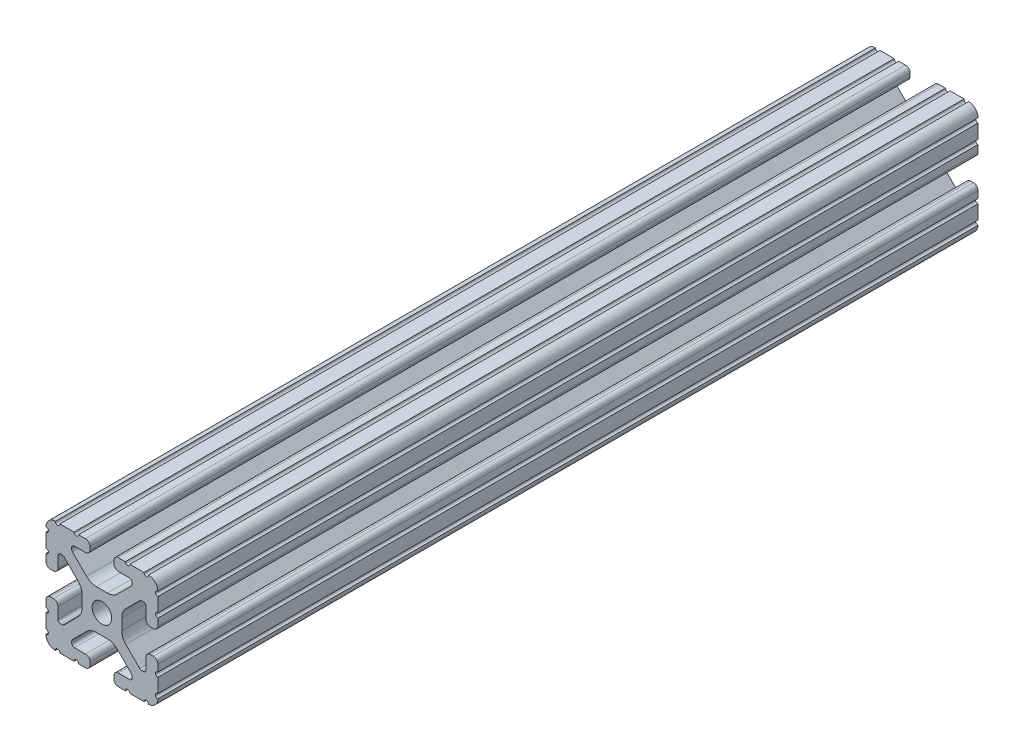
SolidWorks part; units mm, degrees
material "6061 Alloy"
ref_plane "Front Plane" through (0, 0, 0) normal (0, 0, 1) x (1, 0, 0)
ref_plane "Top Plane" through (0, 0, 0) normal (0, 1, 0) x (1, 0, 0)
ref_plane "Right Plane" through (0, 0, 0) normal (1, 0, 0) x (0, 0, -1)
sketch "Sketch1" plane through (0, 0, 0) normal (0, 0, 1) x (1, 0, 0)
  line L0 (0, 25.6181) -> (0, -24.623) construction
  line L1 (-20.8943, 0) -> (20.4607, 0) construction
  line L2 (-10.0229, 12.9148) -> (-5.2522, 8.144)
  line L3 (-10.287, 14.0843) -> (-10.287, 13.5524)
  line L4 (-5.6176, 14.986) -> (-9.3853, 14.986)
  line L5 (-4.064, 17.4964) -> (-4.064, 16.5396)
  line L6 (-7.9742, 19.05) -> (-5.6176, 19.05)
  line L7 (-14.3277, 19.05) -> (-9.4982, 19.05)
  line L8 (-19.05, 9.4961) -> (-19.05, 14.3277)
  line L9 (-19.05, 5.6176) -> (-19.05, 7.9763)
  line L10 (-16.5396, 4.064) -> (-17.4964, 4.064)
  line L11 (-14.986, 9.3853) -> (-14.986, 5.6176)
  line L12 (-13.516, 10.287) -> (-14.0843, 10.287)
  line L13 (-8.1476, 5.2921) -> (-12.8784, 10.0229)
  line L14 (-6.7564, -1.9335) -> (-6.7564, 1.9335)
  line L15 (-12.8784, -10.0229) -> (-8.1476, -5.2921)
  line L16 (-14.0843, -10.287) -> (-13.516, -10.287)
  line L17 (-14.986, -5.6176) -> (-14.986, -9.3853)
  line L18 (-17.4964, -4.064) -> (-16.5396, -4.064)
  line L19 (-19.05, -7.9763) -> (-19.05, -5.6176)
  line L20 (-19.05, -14.3277) -> (-19.05, -9.4961)
  line L21 (-9.4961, -19.05) -> (-14.3277, -19.05)
  line L22 (-5.6176, -19.05) -> (-7.9763, -19.05)
  line L23 (-4.064, -17.4964) -> (-4.064, -16.5396)
  line L24 (10.0229, -12.9148) -> (5.2522, -8.144)
  line L25 (10.287, -14.0843) -> (10.287, -13.5524)
  line L26 (5.6176, -14.986) -> (9.3853, -14.986)
  line L28 (-1.9022, 6.7564) -> (1.9022, 6.7564)
  line L29 (-1.9022, -6.7564) -> (1.9022, -6.7564)
  line L31 (-5.6176, -14.986) -> (-9.3853, -14.986)
  line L32 (-10.287, -14.0843) -> (-10.287, -13.5524)
  line L33 (-10.0229, -12.9148) -> (-5.2522, -8.144)
  line L66 (4.064, -16.5396) -> (4.064, -17.4964)
  line L67 (5.6176, -19.05) -> (7.9763, -19.05)
  line L68 (9.4961, -19.05) -> (14.3277, -19.05)
  line L69 (19.05, -14.3277) -> (19.05, -9.4961)
  line L70 (19.05, -7.9763) -> (19.05, -5.6176)
  line L71 (17.4964, -4.064) -> (16.5396, -4.064)
  line L72 (14.986, -5.6176) -> (14.986, -9.3853)
  line L73 (14.0843, -10.287) -> (13.516, -10.287)
  line L74 (12.8784, -10.0229) -> (8.1476, -5.2921)
  line L75 (6.7564, -1.9335) -> (6.7564, 1.9335)
  line L76 (8.1476, 5.2921) -> (12.8784, 10.0229)
  line L77 (13.516, 10.287) -> (14.0843, 10.287)
  line L78 (14.986, 9.3853) -> (14.986, 5.6176)
  line L79 (16.5396, 4.064) -> (17.4964, 4.064)
  line L80 (19.05, 5.6176) -> (19.05, 7.9763)
  line L81 (19.05, 9.4961) -> (19.05, 14.3277)
  line L82 (14.3277, 19.05) -> (9.4982, 19.05)
  line L83 (7.9742, 19.05) -> (5.6176, 19.05)
  line L84 (4.064, 17.4964) -> (4.064, 16.5396)
  line L85 (5.6176, 14.986) -> (9.3853, 14.986)
  line L86 (10.287, 14.0843) -> (10.287, 13.5524)
  line L87 (10.0229, 12.9148) -> (5.2522, 8.144)
  arc A0 (-10.0229, 12.9148) -> (-10.287, 13.5524) centre (-9.3853, 13.5524) cw
  circle A1 centre (0, 0) radius 3.3274
  arc A2 (-10.287, 14.0843) -> (-9.3853, 14.986) centre (-9.3853, 14.0843) cw
  arc A3 (-4.064, 16.5396) -> (-5.6176, 14.986) centre (-5.6176, 16.5396) cw
  arc A4 (-5.6176, 19.05) -> (-4.064, 17.4964) centre (-5.6176, 17.4964) cw
  arc A5 (-7.9742, 19.05) -> (-9.4982, 19.05) centre (-8.7362, 19.05) cw
  arc A6 (-14.3277, 19.05) -> (-15.8475, 19.05) centre (-15.0876, 18.9933) cw
  arc A7 (-19.05, 15.8475) -> (-15.8475, 19.05) centre (-15.8751, 15.8751) cw
  arc A8 (-19.05, 15.8475) -> (-19.05, 14.3277) centre (-18.9933, 15.0876) cw
  arc A9 (-19.05, 9.4961) -> (-19.05, 7.9763) centre (-18.9933, 8.7362) cw
  arc A10 (-17.4964, 4.064) -> (-19.05, 5.6176) centre (-17.4964, 5.6176) cw
  arc A11 (-14.986, 5.6176) -> (-16.5396, 4.064) centre (-16.5396, 5.6176) cw
  arc A12 (-14.986, 9.3853) -> (-14.0843, 10.287) centre (-14.0843, 9.3853) cw
  arc A13 (-13.516, 10.287) -> (-12.8784, 10.0229) centre (-13.516, 9.3853) cw
  arc A14 (-8.1476, 5.2921) -> (-6.7564, 1.9335) centre (-11.5062, 1.9335) cw
  arc A15 (-6.7564, -1.9335) -> (-8.1476, -5.2921) centre (-11.5062, -1.9335) cw
  arc A16 (-12.8784, -10.0229) -> (-13.516, -10.287) centre (-13.516, -9.3853) cw
  arc A17 (-14.0843, -10.287) -> (-14.986, -9.3853) centre (-14.0843, -9.3853) cw
  arc A18 (-16.5396, -4.064) -> (-14.986, -5.6176) centre (-16.5396, -5.6176) cw
  arc A19 (-19.05, -5.6176) -> (-17.4964, -4.064) centre (-17.4964, -5.6176) cw
  arc A20 (-19.05, -7.9763) -> (-19.05, -9.4961) centre (-18.9933, -8.7362) cw
  arc A21 (-19.05, -14.3277) -> (-19.05, -15.8475) centre (-18.9933, -15.0876) cw
  arc A22 (-15.8475, -19.05) -> (-19.05, -15.8475) centre (-15.8751, -15.8751) cw
  arc A23 (-15.8475, -19.05) -> (-14.3277, -19.05) centre (-15.0876, -18.9933) cw
  arc A24 (-9.4961, -19.05) -> (-7.9763, -19.05) centre (-8.7362, -18.9933) cw
  arc A25 (-4.064, -17.4964) -> (-5.6176, -19.05) centre (-5.6176, -17.4964) cw
  arc A26 (-5.2522, -8.144) -> (-1.9022, -6.7564) centre (-1.9022, -11.494) cw
  arc A27 (1.9022, -6.7564) -> (5.2522, -8.144) centre (1.9022, -11.494) cw
  arc A28 (10.0229, -12.9148) -> (10.287, -13.5524) centre (9.3853, -13.5524) cw
  arc A29 (10.287, -14.0843) -> (9.3853, -14.986) centre (9.3853, -14.0843) cw
  arc A30 (4.064, -16.5396) -> (5.6176, -14.986) centre (5.6176, -16.5396) cw
  arc A31 (-4.064, -16.5396) -> (-5.6176, -14.986) centre (-5.6176, -16.5396) ccw
  arc A32 (-10.287, -14.0843) -> (-9.3853, -14.986) centre (-9.3853, -14.0843) ccw
  arc A33 (-10.0229, -12.9148) -> (-10.287, -13.5524) centre (-9.3853, -13.5524) ccw
  arc A79 (4.064, -17.4964) -> (5.6176, -19.05) centre (5.6176, -17.4964) ccw
  arc A80 (9.4961, -19.05) -> (7.9763, -19.05) centre (8.7362, -18.9933) ccw
  arc A81 (15.8475, -19.05) -> (14.3277, -19.05) centre (15.0876, -18.9933) ccw
  arc A82 (15.8475, -19.05) -> (19.05, -15.8475) centre (15.8751, -15.8751) ccw
  arc A83 (19.05, -14.3277) -> (19.05, -15.8475) centre (18.9933, -15.0876) ccw
  arc A84 (19.05, -7.9763) -> (19.05, -9.4961) centre (18.9933, -8.7362) ccw
  arc A85 (19.05, -5.6176) -> (17.4964, -4.064) centre (17.4964, -5.6176) ccw
  arc A86 (16.5396, -4.064) -> (14.986, -5.6176) centre (16.5396, -5.6176) ccw
  arc A87 (14.0843, -10.287) -> (14.986, -9.3853) centre (14.0843, -9.3853) ccw
  arc A88 (12.8784, -10.0229) -> (13.516, -10.287) centre (13.516, -9.3853) ccw
  arc A89 (6.7564, -1.9335) -> (8.1476, -5.2921) centre (11.5062, -1.9335) ccw
  arc A90 (8.1476, 5.2921) -> (6.7564, 1.9335) centre (11.5062, 1.9335) ccw
  arc A91 (13.516, 10.287) -> (12.8784, 10.0229) centre (13.516, 9.3853) ccw
  arc A92 (14.986, 9.3853) -> (14.0843, 10.287) centre (14.0843, 9.3853) ccw
  arc A93 (14.986, 5.6176) -> (16.5396, 4.064) centre (16.5396, 5.6176) ccw
  arc A94 (17.4964, 4.064) -> (19.05, 5.6176) centre (17.4964, 5.6176) ccw
  arc A95 (19.05, 9.4961) -> (19.05, 7.9763) centre (18.9933, 8.7362) ccw
  arc A96 (19.05, 15.8475) -> (19.05, 14.3277) centre (18.9933, 15.0876) ccw
  arc A97 (19.05, 15.8475) -> (15.8475, 19.05) centre (15.8751, 15.8751) ccw
  arc A98 (14.3277, 19.05) -> (15.8475, 19.05) centre (15.0876, 18.9933) ccw
  arc A99 (7.9742, 19.05) -> (9.4982, 19.05) centre (8.7362, 19.05) ccw
  arc A100 (5.6176, 19.05) -> (4.064, 17.4964) centre (5.6176, 17.4964) ccw
  arc A101 (4.064, 16.5396) -> (5.6176, 14.986) centre (5.6176, 16.5396) ccw
  arc A102 (10.287, 14.0843) -> (9.3853, 14.986) centre (9.3853, 14.0843) ccw
  arc A103 (10.0229, 12.9148) -> (10.287, 13.5524) centre (9.3853, 13.5524) ccw
  arc A104 (1.9022, 6.7564) -> (5.2522, 8.144) centre (1.9022, 11.494) ccw
  arc A105 (-5.2522, 8.144) -> (-1.9022, 6.7564) centre (-1.9022, 11.494) ccw
  dimension "D1" = 6.6548
  dimension "D2" = 19.05
  dimension "D3" = 38.1
  dimension "D4" = 20.574
  dimension "D5" = 13.5128
  dimension "D6" = 4.064
  dimension "D7" = 8.128
  dimension "D8" = 4.064
  dimension "D9" = 12.2936
extrude "Extrude1" add sketch "Sketch1" against normal blind 279.4
